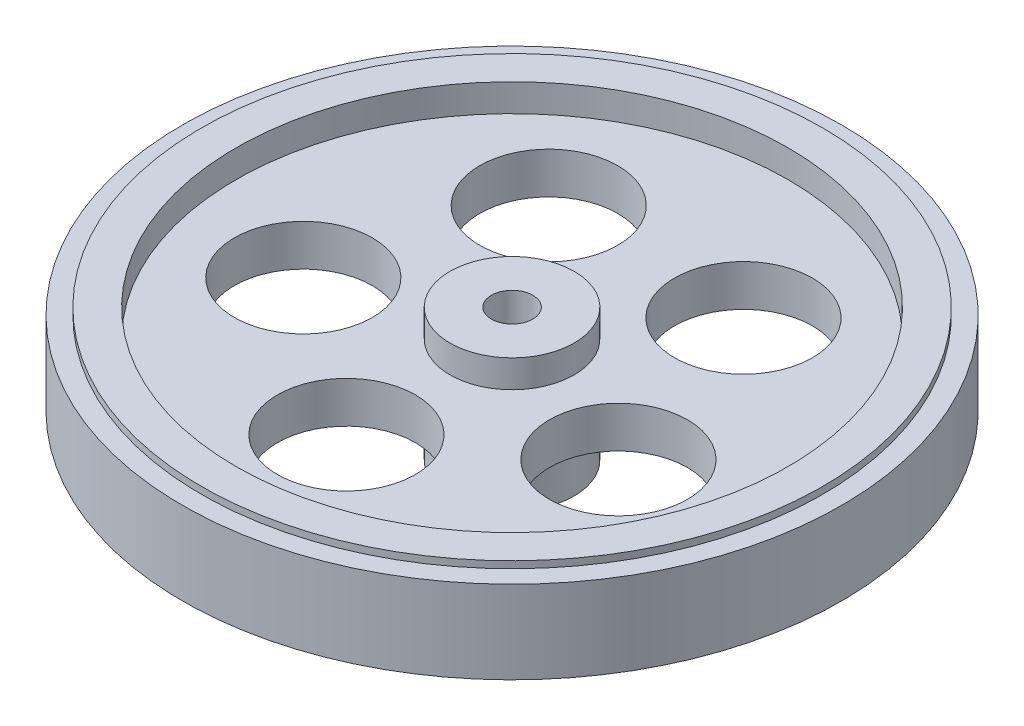
SolidWorks part; units mm, degrees
material "95mm轮子"
ref_plane "前视基准面" through (0, 0, 0) normal (0, 0, 1) x (1, 0, 0)
ref_plane "上视基准面" through (0, 0, 0) normal (0, 1, 0) x (1, 0, 0)
ref_plane "右视基准面" through (0, 0, 0) normal (1, 0, 0) x (0, 0, -1)
other "Configuration Table"
sketch "草图1" plane through (0, 0, 0) normal (0, 0, 1) x (1, 0, 0)
  line L0 (0, 0) -> (0, 45007.2657) construction
  line L1 (-3, 33.9211) -> (-9, 33.9211)
  line L2 (-45, 33.9211) -> (-45, 32.9211)
  line L3 (-45, 32.9211) -> (-47.75, 32.9211)
  line L4 (-47.75, 32.9211) -> (-47.75, 20.9211)
  line L5 (-47.75, 20.9211) -> (-45, 20.9211)
  line L6 (-45, 20.9211) -> (-45, 19.9211)
  line L7 (-45, 19.9211) -> (-40, 19.9211)
  line L8 (-9, 19.9211) -> (-9, 14.7211)
  line L9 (-9, 14.7211) -> (-3, 14.7211)
  line L10 (-3, 14.7211) -> (-3, 33.9211)
  line L11 (-40, 33.9211) -> (-40, 29.9211)
  line L12 (-40, 29.9211) -> (-9, 29.9211)
  line L13 (-9, 29.9211) -> (-9, 33.9211)
  line L14 (-47.75, 26.9211) -> (-3, 26.9211) construction
  line L15 (-40, 33.9211) -> (-45, 33.9211)
  line L16 (-9, 23.9211) -> (-9, 19.9211)
  line L17 (-40, 23.9211) -> (-9, 23.9211)
  line L18 (-40, 19.9211) -> (-40, 23.9211)
  dimension "D1" = 3
  dimension "D2" = 47.75
  dimension "D3" = 45
  dimension "D4" = 45
  dimension "D5" = 12
  dimension "D6" = 14
  dimension "D7" = 1
  dimension "D8" = 9
  dimension "D9" = 4
  dimension "D10" = 5
  dimension "D11" = 19.2
revolve "旋转1" add sketch "草图1" angle 360 about L0
sketch "草图2" plane through (0, 23.9211, 0) normal (0, -1, 0) x (1, 0, 0)
  circle A0 centre (0, 0) radius 24 construction
  circle A1 centre (0, 24) radius 10
  circle A2 centre (22.8254, 7.4164) radius 10
  circle A3 centre (14.1068, -19.4164) radius 10
  circle A4 centre (-14.1068, -19.4164) radius 10
  circle A5 centre (-22.8254, 7.4164) radius 10
  dimension "D1" = 48
  dimension "D2" = 20
  dimension "D3" = 5
extrude "切除-拉伸1" cut sketch "草图2" against normal blind 10
